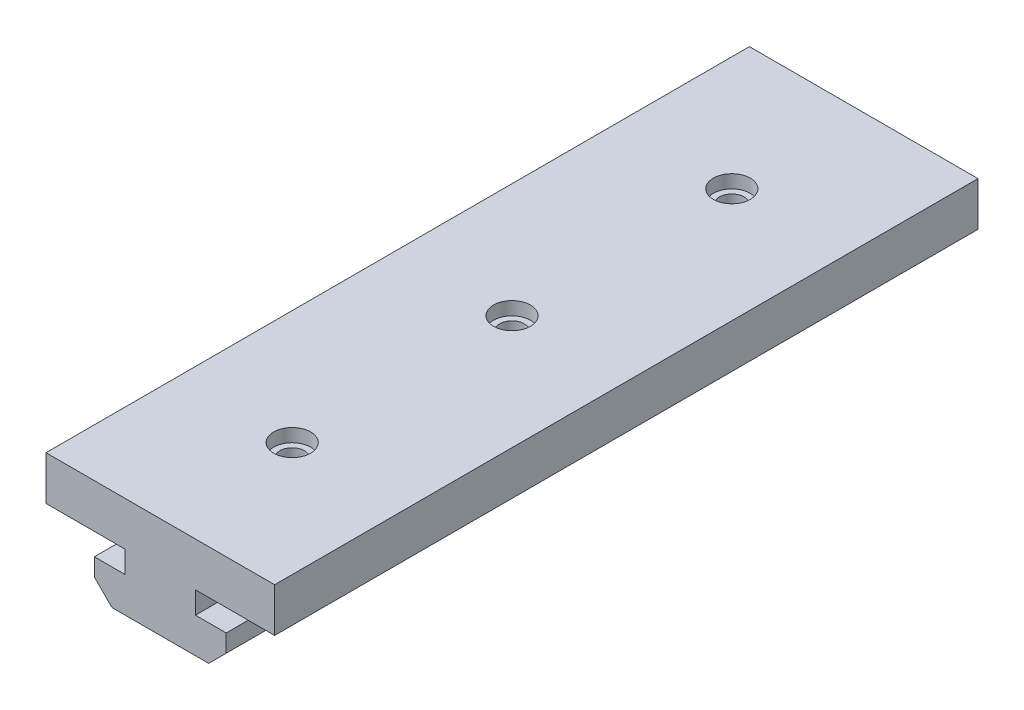
SolidWorks part; units mm, degrees
material "6061 Alloy"
ref_plane "Front Plane" through (0, 0, 0) normal (0, 0, 1) x (1, 0, 0)
ref_plane "Top Plane" through (0, 0, 0) normal (0, 1, 0) x (1, 0, 0)
ref_plane "Right Plane" through (0, 0, 0) normal (1, 0, 0) x (0, 0, -1)
sketch "Sketch1" plane through (0, 0, 0) normal (0, 0, 1) x (1, 0, 0)
  line L28 (-13, 0) -> (-4, 0)
  line L29 (-4, 0) -> (-4, -2.5)
  line L30 (-4, -2.5) -> (-7.5, -2.5)
  line L31 (-7.5, -2.5) -> (-7.5, -4.5)
  line L32 (-7.5, -4.5) -> (-5.5, -6.5)
  line L33 (-5.5, -6.5) -> (5.5, -6.5)
  line L34 (5.5, -6.5) -> (7.5, -4.5)
  line L35 (7.5, -4.5) -> (7.5, -2.5)
  line L36 (7.5, -2.5) -> (4, -2.5)
  line L37 (4, -2.5) -> (4, 0)
  line L38 (4, 0) -> (13, 0)
  line L39 (13, 0) -> (13, 5)
  line L40 (13, 5) -> (-13, 5)
  line L41 (-13, 5) -> (-13, 0)
extrude "Extrude1" add sketch "Sketch1" along normal blind 80
sketch "Sketch2" plane through (0, 5, 0) normal (0, 1, 0) x (-1, 0, 0)
  line L0 (-13, 80) -> (13, 80) construction
  point P0 (0, 65)
  point P1 (0, 40)
  point P2 (0, 15)
  dimension "D1" = 15
  dimension "D2" = 40
  dimension "D3" = 65
hole_wizard "CBORE for M5 Hex Head Cap Screw1" positions "3DSketch1" profile "Sketch3" counterbore size "M5" standard "ANSI Metric" end condition through all
sketch3d "3DSketch1"
  point P0 (0, 5, 65)
  point P2 (0, 5, 40)
  point P4 (0, 5, 15)
sketch "Sketch3" plane through (0, 5, 65) normal (1, 0, 0) x (0, 0, 1)
  line L0 (0, 0) -> (0, 11.5)
  line L1 (0, 11.5) -> (1.4, 11.5)
  line L2 (0, 5.75) -> (1.7603, 5.75) construction
  line L3 (1.4, 10) -> (1.4, 1.5)
  line L4 (1.4, 1.5) -> (2.1, 1.5)
  line L5 (2.1, 1.5) -> (2.1, 0)
  line L6 (2.1, 10) -> (2.1, 11.5)
  line L7 (2.1, 0) -> (0, 0)
  line L8 (1.4, 10) -> (2.1, 10)
  line L9 (1.4, 11.5) -> (2.1, 11.5)
  line L11 (0, -6.35) -> (0, 107.95) construction
  dimension "Thru Hole Dia." = 2.8
  dimension "Thru Hole Depth" = 11.5
  dimension "C'Bore Dia." = 4.2
  dimension "C'Bore Depth" = 1.5
